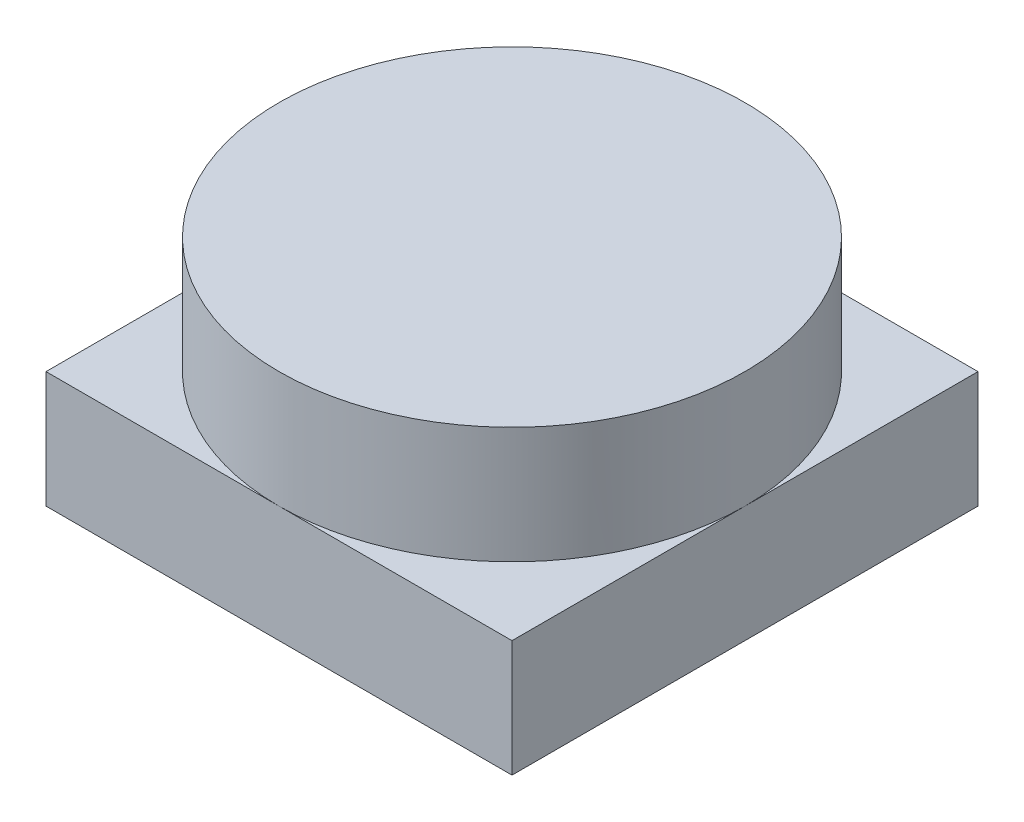
SolidWorks part; units mm, degrees
ref_plane "Front Plane" through (0, 0, 0) normal (0, 0, 1) x (1, 0, 0)
ref_plane "Top Plane" through (0, 0, 0) normal (0, 1, 0) x (1, 0, 0)
ref_plane "Right Plane" through (0, 0, 0) normal (1, 0, 0) x (0, 0, -1)
sketch "Sketch1" plane through (0, 0, 0) normal (0, 1, 0) x (1, 0, 0)
  circle A0 centre (0, 0) radius 10
  dimension "D1" = 20
extrude "Boss-Extrude1" add sketch "Sketch1" along normal blind 10
sketch "Sketch2" plane through (0, 0, 0) normal (0, 1, 0) x (1, 0, 0)
  line L1 (-10, -10) -> (10, -10)
  line L2 (-10, -10) -> (-10, 10)
  line L3 (-10, 10) -> (10, 10)
  line L4 (10, -10) -> (10, 10)
  line L5 (-10, -10) -> (10, 10) construction
  line L6 (-10, 10) -> (10, -10) construction
  point P0 (0, 0)
  dimension "D1" = 20
  dimension "D2" = 20
extrude "Boss-Extrude2" add sketch "Sketch2" along normal blind 5
